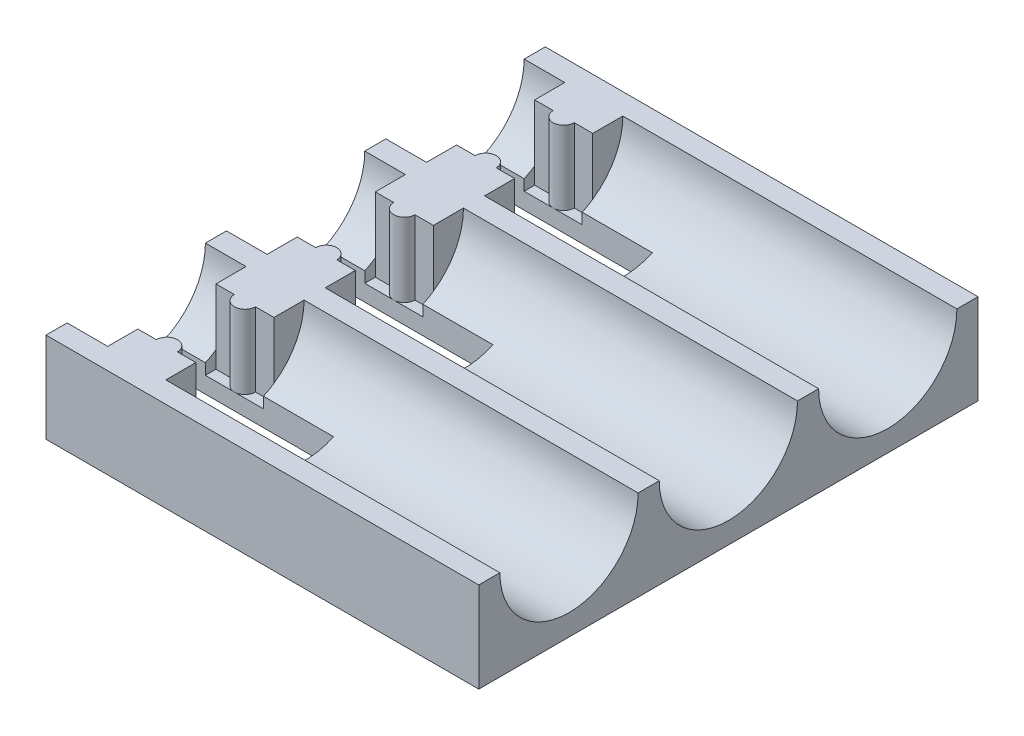
SolidWorks part; units mm, degrees
ref_plane "Front Plane" through (0, 0, 0) normal (0, 0, 1) x (1, 0, 0)
ref_plane "Top Plane" through (0, 0, 0) normal (0, 1, 0) x (1, 0, 0)
ref_plane "Right Plane" through (0, 0, 0) normal (1, 0, 0) x (0, 0, -1)
sketch "Sketch1" plane through (0, 0, 0) normal (1, 0, 0) x (0, 0, -1)
  line L0 (-8.55, 0) -> (-6.55, 0)
  line L1 (-6.55, 0) -> (6.55, 0) construction
  line L2 (6.55, 0) -> (8.55, 0)
  line L3 (-21.65, 0) -> (-8.55, 0) construction
  line L4 (8.55, 0) -> (21.65, 0) construction
  line L5 (-21.65, 0) -> (-23.65, 0)
  line L6 (-23.65, 0) -> (-23.65, -8.55)
  line L7 (-23.65, -8.55) -> (23.65, -8.55)
  line L8 (23.65, -8.55) -> (23.65, 0)
  line L9 (23.65, 0) -> (21.65, 0)
  line L10 (0, -6.55) -> (0, -8.55) construction
  arc A0 (-6.55, 0) -> (6.55, 0) centre (0, 0) ccw
  arc A1 (-21.65, 0) -> (-8.55, 0) centre (-15.1, 0) ccw
  arc A2 (8.55, 0) -> (21.65, 0) centre (15.1, 0) ccw
  dimension "D1" = 13.1
  dimension "D2" = 2
extrude "Boss-Extrude1" add sketch "Sketch1" along normal blind 41
sketch "Sketch2" plane through (0, 0, 0) normal (0, 1, 0) x (1, 0, 0)
  line L0 (6.6, -3.7) -> (6.6, 3.7) construction
  line L1 (5.6, -3.7) -> (5.6, 3.7) construction
  line L2 (0, -7.55) -> (41, -7.55) construction
  line L3 (0, -6.55) -> (0, -8.55) construction
  line L4 (41, -6.55) -> (41, -8.55) construction
  line L5 (0, 7.55) -> (41, 7.55) construction
  line L6 (0, 8.55) -> (0, 6.55) construction
  line L7 (41, 8.55) -> (41, 6.55) construction
  circle A2 centre (6.6, 3.7) radius 1
  circle A3 centre (6.6, -3.7) radius 1
  circle A4 centre (6.6, -11.4) radius 1
  circle A5 centre (6.6, -18.8) radius 1
  circle A6 centre (6.6, 18.8) radius 1
  circle A7 centre (6.6, 11.4) radius 1
  point P4 (6.6, 0)
  point P20 (0, 7.55)
  dimension "D2" = 2
  dimension "D1" = 5.6
  dimension "D3" = 7.4
extrude "Boss-Extrude2" add sketch "Sketch2" against normal up to next
sketch "Sketch4" plane through (0, 0, 0) normal (0, 1, 0) x (1, 0, 0)
  line L0 (41, -6.55) -> (0, -6.55) construction
  line L1 (3.85, -6.55) -> (9.35, -6.55)
  line L2 (3.85, -6.55) -> (3.85, 6.55)
  line L3 (3.85, 6.55) -> (9.35, 6.55)
  line L4 (9.35, -6.55) -> (9.35, 6.55)
  line L5 (41, 6.55) -> (0, 6.55) construction
  line L6 (6.6, -3.7) -> (6.6, 3.7) construction
  line L7 (9.35, 0) -> (3.85, 0) construction
  line L8 (0, -7.55) -> (41, -7.55) construction
  line L9 (0, -6.55) -> (0, -8.55) construction
  line L10 (41, -6.55) -> (41, -8.55) construction
  line L11 (0, 7.55) -> (41, 7.55) construction
  line L12 (0, 8.55) -> (0, 6.55) construction
  line L13 (41, 8.55) -> (41, 6.55) construction
  line L14 (3.85, -21.65) -> (9.35, -21.65)
  line L15 (9.35, -8.55) -> (9.35, -21.65)
  line L16 (3.85, -8.55) -> (9.35, -8.55)
  line L17 (3.85, -8.55) -> (3.85, -21.65)
  line L18 (3.85, 8.55) -> (9.35, 8.55)
  line L19 (9.35, 21.65) -> (9.35, 8.55)
  line L20 (3.85, 21.65) -> (9.35, 21.65)
  line L21 (3.85, 21.65) -> (3.85, 8.55)
  circle A0 centre (6.6, 3.7) radius 1 construction
  circle A1 centre (6.6, -3.7) radius 1 construction
  circle A2 centre (6.6, 3.7) radius 1
  circle A3 centre (6.6, -3.7) radius 1
  circle A4 centre (6.6, -11.4) radius 1
  circle A5 centre (6.6, -18.8) radius 1
  circle A6 centre (6.6, 11.4) radius 1
  circle A7 centre (6.6, 18.8) radius 1
  point P16 (6.6, 0)
  point P17 (6.6, 0)
  dimension "D1" = 5.5
extrude "Cut-Extrude1" cut sketch "Sketch4" against normal blind 7
sketch "Sketch6" plane through (0, 0, 0) normal (0, 1, 0) x (1, 0, 0)
  line L0 (0, 0) -> (41, 0) construction
  line L1 (3.85, -3.7) -> (9.35, -3.7)
  line L2 (9.35, -3.7) -> (9.35, -6.55)
  line L3 (9.35, -6.55) -> (3.85, -6.55)
  line L4 (3.85, -6.55) -> (3.85, -3.7)
  line L5 (7.6, -3.7) -> (5.6, -3.7) construction
  line L6 (7.6, 3.7) -> (5.6, 3.7) construction
  line L7 (3.85, 6.55) -> (3.85, 3.7)
  line L8 (9.35, 6.55) -> (3.85, 6.55)
  line L9 (9.35, 3.7) -> (9.35, 6.55)
  line L10 (3.85, 3.7) -> (9.35, 3.7)
  line L11 (0, -7.55) -> (41, -7.55) construction
  line L12 (0, 7.55) -> (41, 7.55) construction
  line L13 (0, -6.55) -> (0, -8.55) construction
  line L14 (0, 8.55) -> (0, 6.55) construction
  line L15 (41, 8.55) -> (41, 6.55) construction
  line L16 (41, -6.55) -> (41, 6.55) construction
  line L17 (41, -6.55) -> (41, -8.55) construction
  line L18 (9.35, -6.55) -> (9.35, 6.55) construction
  line L19 (5.6, -3.7) -> (7.6, -3.7) construction
  line L20 (5.6, -11.4) -> (7.6, -11.4) construction
  line L21 (7.6, -18.8) -> (5.6, -18.8) construction
  line L22 (7.6, -11.4) -> (5.6, -11.4) construction
  line L23 (3.85, -18.8) -> (9.35, -18.8)
  line L24 (9.35, -18.8) -> (9.35, -21.65)
  line L25 (9.35, -21.65) -> (3.85, -21.65)
  line L26 (3.85, -21.65) -> (3.85, -18.8)
  line L27 (3.85, -8.55) -> (3.85, -11.4)
  line L28 (9.35, -8.55) -> (3.85, -8.55)
  line L29 (9.35, -11.4) -> (9.35, -8.55)
  line L30 (3.85, -11.4) -> (9.35, -11.4)
  line L31 (5.6, 18.8) -> (7.6, 18.8) construction
  line L32 (7.6, 11.4) -> (5.6, 11.4) construction
  line L33 (7.6, 18.8) -> (5.6, 18.8) construction
  line L34 (3.85, 11.4) -> (9.35, 11.4)
  line L35 (9.35, 11.4) -> (9.35, 8.55)
  line L36 (9.35, 8.55) -> (3.85, 8.55)
  line L37 (3.85, 8.55) -> (3.85, 11.4)
  line L38 (3.85, 21.65) -> (3.85, 18.8)
  line L39 (9.35, 21.65) -> (3.85, 21.65)
  line L40 (9.35, 18.8) -> (9.35, 21.65)
  line L41 (3.85, 18.8) -> (9.35, 18.8)
  circle A0 centre (6.6, -3.7) radius 1 construction
  circle A1 centre (6.6, -3.7) radius 1 construction
extrude "Boss-Extrude4" add sketch "Sketch6" against normal up to surface (7 mm away) up to face at (6.6, -7, -19.8)
sketch "Sketch7" plane through (0, -7, 0) normal (0, 1, 0) x (1, 0, 0)
  line L0 (0, 6.55) -> (0, -6.55) construction
  line L1 (0, -2.7) -> (16, -2.7)
  line L2 (0, -2.7) -> (0, 2.7)
  line L3 (0, 2.7) -> (16, 2.7)
  line L6 (16, -2.7) -> (16, 2.7)
  line L7 (0, 7.55) -> (41, 7.55) construction
  line L8 (0, 8.55) -> (0, 6.55) construction
  line L9 (41, 8.55) -> (41, 6.55) construction
  line L10 (16, -12.4) -> (16, -17.8)
  line L11 (0, -6.55) -> (0, -8.55) construction
  line L12 (0, -7.55) -> (41, -7.55) construction
  line L13 (41, -6.55) -> (41, -8.55) construction
  line L14 (0, -17.8) -> (16, -17.8)
  line L15 (0, -12.4) -> (0, -17.8)
  line L16 (0, -12.4) -> (16, -12.4)
  line L17 (0, 17.8) -> (0, 12.4)
  line L18 (0, 12.4) -> (16, 12.4)
  line L19 (16, 17.8) -> (16, 12.4)
  line L20 (0, 17.8) -> (16, 17.8)
  circle A0 centre (6.6, 3.7) radius 1 construction
  circle A1 centre (6.6, -3.7) radius 1 construction
  dimension "D1" = 16
extrude "Cut-Extrude2" cut sketch "Sketch7" against normal through all both and the other way through all
